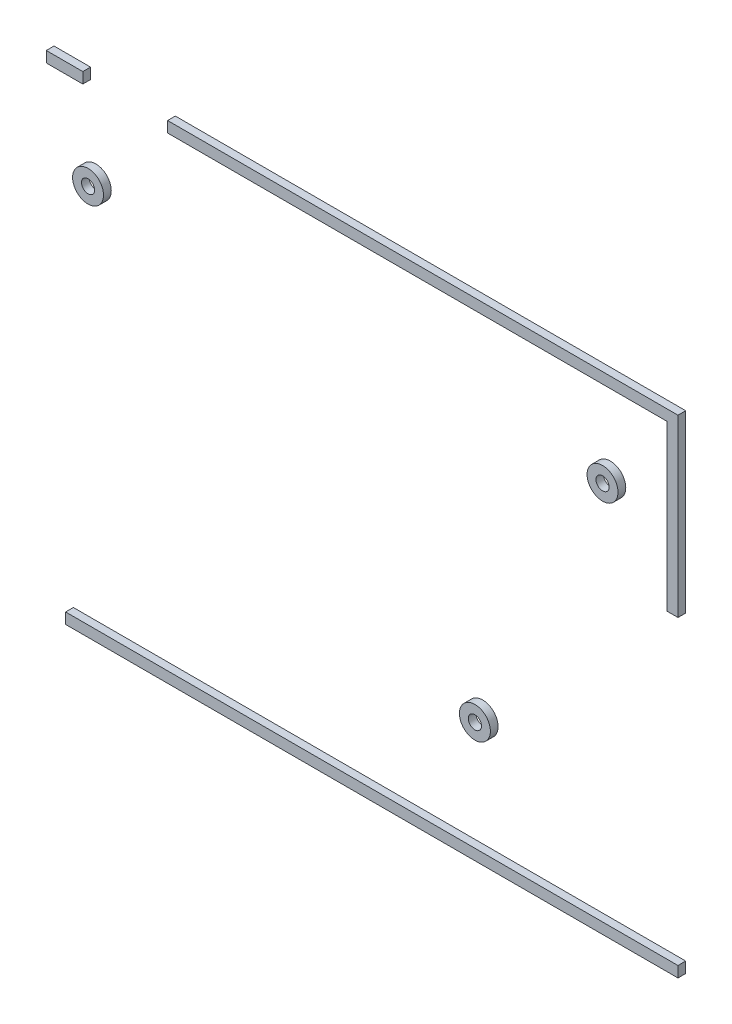
SolidWorks part; units mm, degrees
material "Custom Plastic"
ref_plane "Front Plane" through (0, 0, 0) normal (0, 0, 1) x (1, 0, 0)
ref_plane "Top Plane" through (0, 0, 0) normal (0, 1, 0) x (1, 0, 0)
ref_plane "Right Plane" through (0, 0, 0) normal (1, 0, 0) x (0, 0, -1)
sketch "Sketch1" plane through (0, 0, 0) normal (0, 0, 1) x (1, 0, 0)
  line L0 (44.0608, 63.2) -> (44.0608, 60.2) construction
  line L1 (17.7, -60.2) -> (176, -60.2)
  line L2 (17.7, -60.2) -> (17.7, -63)
  line L3 (17.7, -63) -> (176, -63)
  line L4 (176, -60.2) -> (176, -63)
  line L5 (173.2, 17.7) -> (176, 17.7)
  line L6 (173.2, 17.7) -> (173.2, 63)
  line L7 (173.2, 63) -> (176, 63)
  line L8 (176, 17.7) -> (176, 63)
  line L9 (173.2, 63) -> (44.0608, 63)
  line L10 (173.2, 63) -> (173.2, 60.2)
  line L11 (173.2, 60.2) -> (44.0608, 60.2)
  line L12 (44.0608, 63) -> (44.0608, 60.2)
  line L13 (44.0608, 60.2) -> (173.2, 60.2) construction
  line L14 (22.1392, 63.2) -> (22.1392, 60.2) construction
  line L15 (12.7, 60.2) -> (22.1392, 60.2)
  line L16 (12.7, 60.2) -> (12.7, 63)
  line L17 (12.7, 63) -> (22.1392, 63)
  line L18 (22.1392, 60.2) -> (22.1392, 63)
  line L19 (176, 63) -> (-176, 63) construction
  circle A0 centre (123.5, -32) radius 4
  circle A1 centre (156.5, 38) radius 4
  circle A2 centre (23.5, 38) radius 4
  circle A3 centre (23.5, 38) radius 4 construction
  circle A4 centre (156.5, 38) radius 4 construction
  circle A5 centre (123.5, -32) radius 4 construction
  circle A6 centre (23.5, 38) radius 1.7
  circle A7 centre (156.5, 38) radius 1.7
  circle A8 centre (123.5, -32) radius 1.7
  dimension "D1" = 3.4
  dimension "D2" = 3.4
  dimension "D3" = 3.4
extrude "Boss-Extrude1" add sketch "Sketch1" along normal up to surface (2 mm away) contours L9 L12 L11 L6 | L15 L18 L17 L16 | A2 A6 | L5 L8 L7 L6 | A1 A7 | A0 A8 | L4 L1 L2 L3
